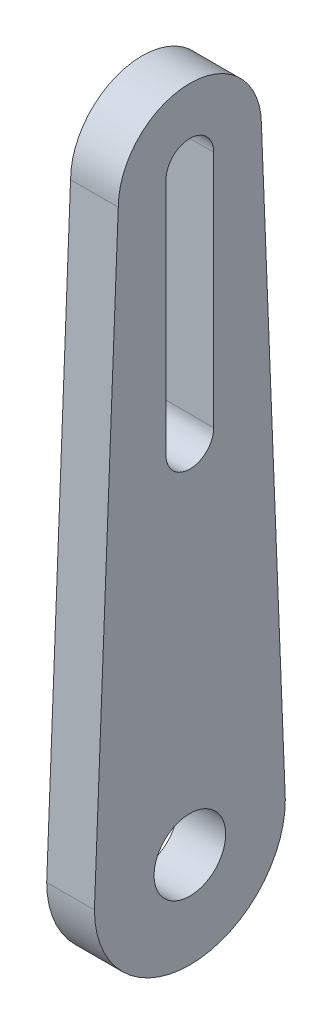
SolidWorks part; units mm, degrees
material "ABS"
ref_plane "Front Plane" through (0, 0, 0) normal (0, 0, 1) x (1, 0, 0)
ref_plane "Top Plane" through (0, 0, 0) normal (0, 1, 0) x (1, 0, 0)
ref_plane "Right Plane" through (0, 0, 0) normal (1, 0, 0) x (0, 0, -1)
sketch "Sketch1" plane through (0, 0, 0) normal (1, 0, 0) x (0, 0, -1)
  line L0 (0, 0) -> (0, 50) construction
  line L1 (0, 50) -> (0, 30) construction
  line L2 (2, 50) -> (2, 30)
  line L3 (-2, 50) -> (-2, 30)
  line L4 (0, 50) -> (6, 50) construction
  line L5 (0, 50) -> (-6, 50) construction
  line L6 (0, 0) -> (8, 0) construction
  line L7 (0, 0) -> (-8, 0) construction
  line L8 (-8, 0) -> (-6, 50)
  line L9 (6, 50) -> (8, 0)
  circle A0 centre (0, 0) radius 3
  arc A1 (-8, 0) -> (8, 0) centre (0, 0) ccw
  arc A2 (2, 50) -> (-2, 50) centre (0, 50) ccw
  arc A3 (-2, 30) -> (2, 30) centre (0, 30) ccw
  arc A4 (-6, 50) -> (6, 50) centre (0, 50) cw
  point P5 (0, 40)
  point P15 (6, 47.8163)
  dimension "D1" = 4
  dimension "D2" = 6
  dimension "D3" = 8
  dimension "D4" = 6
  dimension "D5" = 20
  dimension "D6" = 50
extrude "Boss-Extrude1" add sketch "Sketch1" along normal mid plane 4
